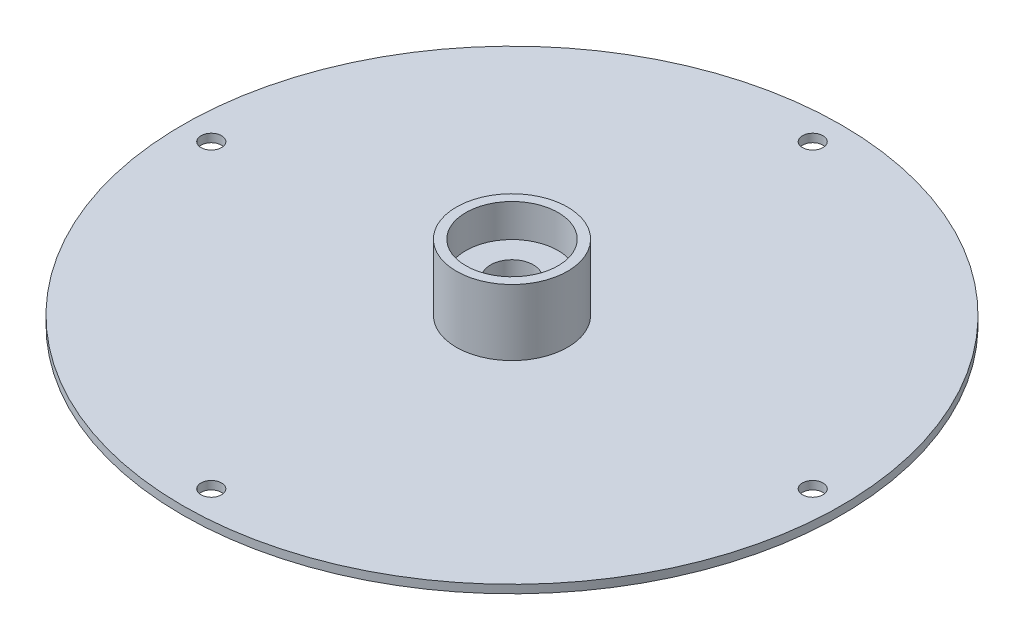
SolidWorks part; units mm, degrees
ref_plane "Front Plane" through (0, 0, 0) normal (0, 0, 1) x (1, 0, 0)
ref_plane "Top Plane" through (0, 0, 0) normal (0, 1, 0) x (1, 0, 0)
ref_plane "Right Plane" through (0, 0, 0) normal (1, 0, 0) x (0, 0, -1)
sketch "Sketch1" plane through (0, 0, 0) normal (0, 1, 0) x (1, 0, 0)
  circle A0 centre (0, 0) radius 80
  circle A1 centre (0, 0) radius 5.2
  dimension "D1" = 160
  dimension "D2" = 10.4
extrude "Boss-Extrude1" add sketch "Sketch1" along normal blind 2
sketch "Sketch2" plane through (0, 2, 0) normal (0, 1, 0) x (1, 0, 0)
  line L0 (0, 0) -> (0, 73) construction
  line L1 (0, 0) -> (73, 0) construction
  line L2 (0, 0) -> (0, -73) construction
  line L3 (0, 0) -> (-73, 0) construction
  circle A0 centre (0, 73) radius 2.5
  circle A1 centre (73, 0) radius 2.5
  circle A2 centre (0, -73) radius 2.5
  circle A3 centre (-73, 0) radius 2.5
  point P13 (0, 0)
  dimension "D2" = 5
  dimension "D1" = 73
  dimension "D3" = 4
extrude "Cut-Extrude1" cut sketch "Sketch2" against normal through all
sketch "Sketch3" plane through (0, 2, 0) normal (0, 1, 0) x (1, 0, 0)
  circle A1 centre (0, 0) radius 13.5
  circle A2 centre (0, 0) radius 5.2
  circle A3 centre (0, 0) radius 5.2
  dimension "D2" = 27
  dimension "D1" = 0
extrude "Boss-Extrude2" add sketch "Sketch3" along normal blind 8
sketch "Sketch4" plane through (0, 10, 0) normal (0, 1, 0) x (1, 0, 0)
  circle A1 centre (0, 0) radius 11.2
  circle A2 centre (0, 0) radius 13.5
  circle A3 centre (0, 0) radius 13.5
  dimension "D2" = 22.4
  dimension "D1" = 0
extrude "Boss-Extrude3" add sketch "Sketch4" along normal blind 8
